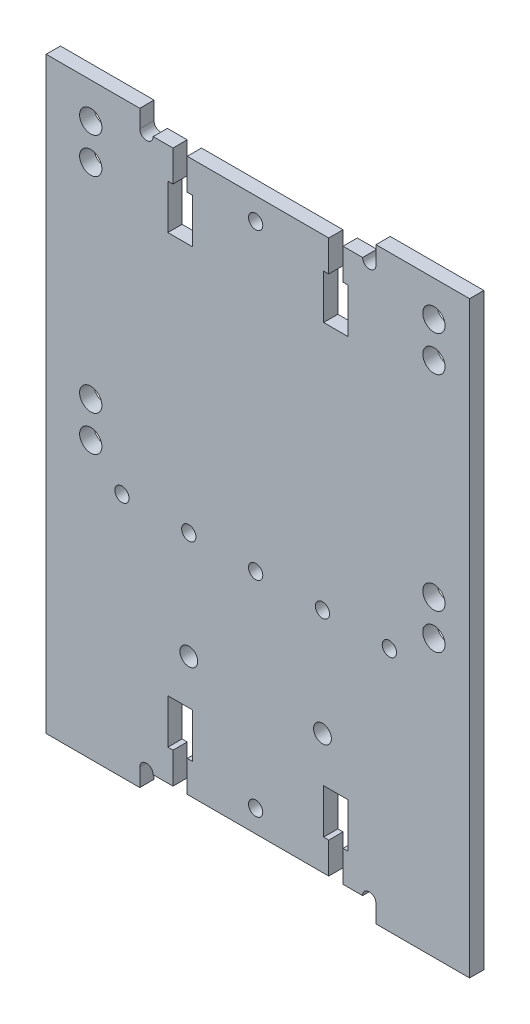
SolidWorks part; units mm, degrees
ref_plane "Front Plane" through (0, 0, 0) normal (0, 0, 1) x (1, 0, 0)
ref_plane "Top Plane" through (0, 0, 0) normal (0, 1, 0) x (1, 0, 0)
ref_plane "Right Plane" through (0, 0, 0) normal (1, 0, 0) x (0, 0, -1)
sketch "Model" plane through (0, 0, 0) normal (0, 0, 1) x (1, 0, 0)
  line L0 (15.75, 55) -> (15.75, 45)
  line L1 (-24.7, -55) -> (-24.7, -45)
  line L2 (14.6, 55) -> (15.75, 55)
  line L3 (15.75, -55) -> (15.75, -45)
  line L4 (10.25, -55) -> (10.25, -45)
  line L5 (-20.35, -62) -> (11.4, -62)
  line L6 (-20.35, -55) -> (-19.2, -55)
  line L7 (-52, -66) -> (-31, -66)
  line L8 (22, -66) -> (43, -66)
  line L9 (-23.55, -62) -> (-23.55, -55)
  line L10 (22, 66) -> (43, 66)
  line L11 (14.6, -62) -> (14.6, -55)
  line L12 (-20.35, 62) -> (11.4, 62)
  line L13 (-20.35, 55) -> (-19.2, 55)
  line L14 (-19.2, 55) -> (-19.2, 45)
  line L15 (-52, -66) -> (-52, 66)
  line L16 (-24.7, 55) -> (-23.55, 55)
  line L17 (43, -66) -> (43, 66)
  line L18 (11.4, 62) -> (11.4, 55)
  line L19 (10.25, -45) -> (15.75, -45)
  line L20 (22, 66) -> (22, 62)
  line L21 (-20.35, 62) -> (-20.35, 55)
  line L22 (-24.7, -55) -> (-23.55, -55)
  line L23 (-31, -62) -> (-23.55, -62)
  line L24 (10.25, 55) -> (11.4, 55)
  line L25 (14.6, -62) -> (22, -62)
  line L26 (14.6, 62) -> (14.6, 55)
  line L27 (11.4, -62) -> (11.4, -55)
  line L28 (-24.7, 55) -> (-24.7, 45)
  line L29 (-31, -66) -> (-31, -62)
  line L30 (14.6, 62) -> (22, 62)
  line L31 (22, -66) -> (22, -62)
  line L32 (-19.2, -55) -> (-19.2, -45)
  line L33 (10.25, 45) -> (15.75, 45)
  line L34 (-24.7, 45) -> (-19.2, 45)
  line L35 (-20.35, -62) -> (-20.35, -55)
  line L36 (14.6, -55) -> (15.75, -55)
  line L37 (-24.7, -45) -> (-19.2, -45)
  line L38 (-52, 66) -> (-31, 66)
  line L39 (10.25, -55) -> (11.4, -55)
  line L40 (-31, 62) -> (-23.55, 62)
  line L41 (-31, 66) -> (-31, 62)
  line L42 (-23.55, 62) -> (-23.55, 55)
  line L43 (10.25, 55) -> (10.25, 45)
  circle A0 centre (-42, -4) radius 2.5
  circle A1 centre (-42, 58) radius 2.5
  circle A2 centre (35, 50) radius 2.5
  circle A3 centre (35, -4) radius 2.5
  circle A4 centre (35, 58) radius 2.5
  circle A5 centre (35, 4) radius 2.5
  circle A6 centre (-42, 4) radius 2.5
  circle A7 centre (-42, 50) radius 2.5
  circle A8 centre (-20, -35) radius 2
  circle A9 centre (10, -35) radius 2
  circle A11 centre (10, -11) radius 1.6
  circle A14 centre (25, -11) radius 1.6
  circle A15 centre (-5, 57) radius 1.6
  circle A16 centre (-5, -57) radius 1.6
  circle A18 centre (-35, -11) radius 1.6
  circle A19 centre (-20, -11) radius 1.6
  circle A20 centre (-5, -11) radius 1.6
extrude "Boss-Extrude1" add sketch "Model" along normal blind 3.2
sketch "Sketch1" plane through (0, 0, 3.2) normal (0, 0, 1) x (1, 0, 0)
  line L0 (-23.55, 62) -> (-31, 62) construction
  line L1 (22, 62) -> (14.6, 62) construction
  line L2 (14.6, -62) -> (22, -62) construction
  line L3 (-31, -62) -> (-23.55, -62) construction
  circle A0 centre (-29.4995, 62) radius 1.5005
  circle A1 centre (20.4995, 62) radius 1.5005
  circle A2 centre (20.4995, -62) radius 1.5005
  circle A3 centre (-29.4995, -62) radius 1.5005
  dimension "D1" = 3.001
  dimension "D2" = 3.001
  dimension "D3" = 3.001
  dimension "D4" = 3.001
extrude "Cut-Extrude1" cut sketch "Sketch1" against normal through all
equation "\"dim\"= 3.001"
equation "\"D2@Sketch1\"=\"dim\""
equation "\"D1@Sketch1\"=\"dim\""
equation "\"D3@Sketch1\"=\"dim\""
equation "\"D4@Sketch1\"=\"dim\""
